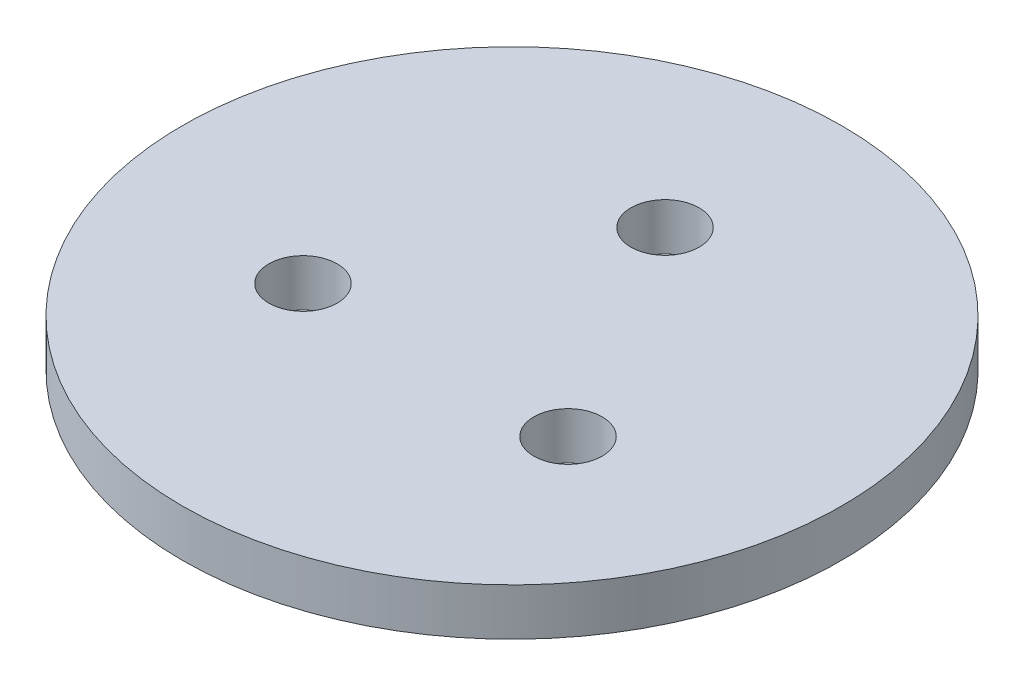
SolidWorks part; units mm, degrees
ref_plane "Plan de face" through (0, 0, 0) normal (0, 0, 1) x (1, 0, 0)
ref_plane "Plan de dessus" through (0, 0, 0) normal (0, 1, 0) x (1, 0, 0)
ref_plane "Plan de droite" through (0, 0, 0) normal (1, 0, 0) x (0, 0, -1)
sketch "Esquisse4" plane through (0, 0, 0) normal (0, 1, 0) x (1, 0, 0)
  circle A0 centre (0, 0) radius 14
  dimension "D1" = 28
extrude "Boss.-Extru.1" add sketch "Esquisse4" along normal mid plane 2
hole_wizard "Dégagement M2.51" positions "Esquisse9" profile "Esquisse8" hole size "M2.5" standard "DIN" end condition through all
sketch "Esquisse9" plane through (0, 1, 0) normal (0, 1, 0) x (1, 0, 0)
  line L0 (0, -6.5) -> (0, 6.5) construction
  point P4 (0, 6.5)
  dimension "D1" = 13
sketch "Esquisse8" plane through (0, 1, -6.5) normal (1, 0, 0) x (0, 0, 1)
  line L0 (0, 0) -> (0, 2)
  line L1 (0, 2) -> (1.45, 2)
  line L2 (1.45, 2) -> (1.45, 0)
  line L5 (1.45, 0) -> (0, 0)
  line L11 (0, -6.35) -> (0, 107.95) construction
  dimension "Diamètre du perçage jusqu'au prochain" = 2.9
  dimension "Profondeur du perçage jusqu'au prochain" = 2
pattern_circular "Répétition circulaire1" count 3 over 360 about axis through (0, 0, 0) along (0, 1, 0) of "Dégagement M2.51"
